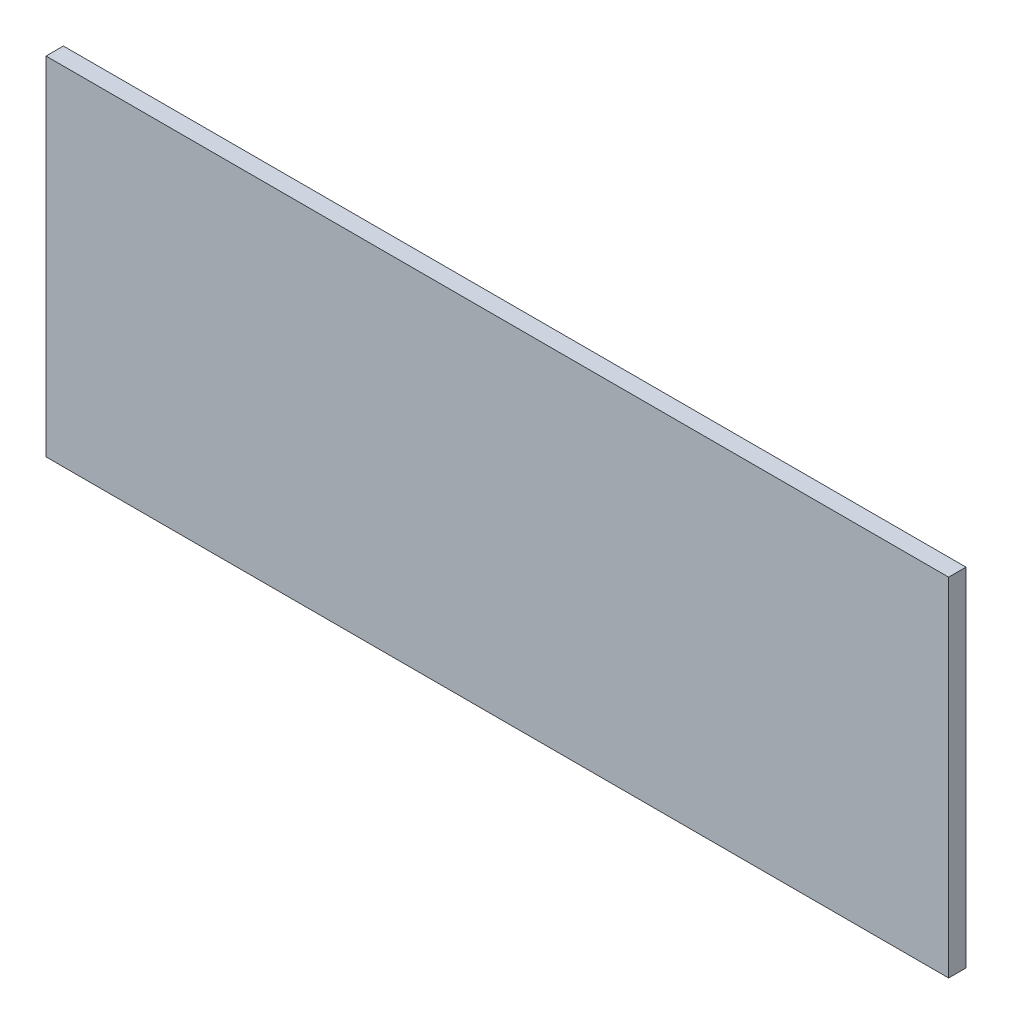
SolidWorks part; units mm, degrees
ref_plane "Plan de face" through (0, 0, 0) normal (0, 0, 1) x (1, 0, 0)
ref_plane "Plan de dessus" through (0, 0, 0) normal (0, 1, 0) x (1, 0, 0)
ref_plane "Plan de droite" through (0, 0, 0) normal (1, 0, 0) x (0, 0, -1)
sketch "Esquisse1" plane through (0, 0, 0) normal (0, 0, 1) x (1, 0, 0)
  line L1 (-76.5, -7.5155) -> (79.5, -7.5155)
  line L2 (-76.5, -7.5155) -> (-76.5, 52.4845)
  line L3 (-76.5, 52.4845) -> (79.5, 52.4845)
  line L4 (79.5, -7.5155) -> (79.5, 52.4845)
  point P0 (0, 0)
  dimension "D1" = 156
  dimension "D2" = 60
extrude "Boss.-Extru.1" add sketch "Esquisse1" along normal blind 3
